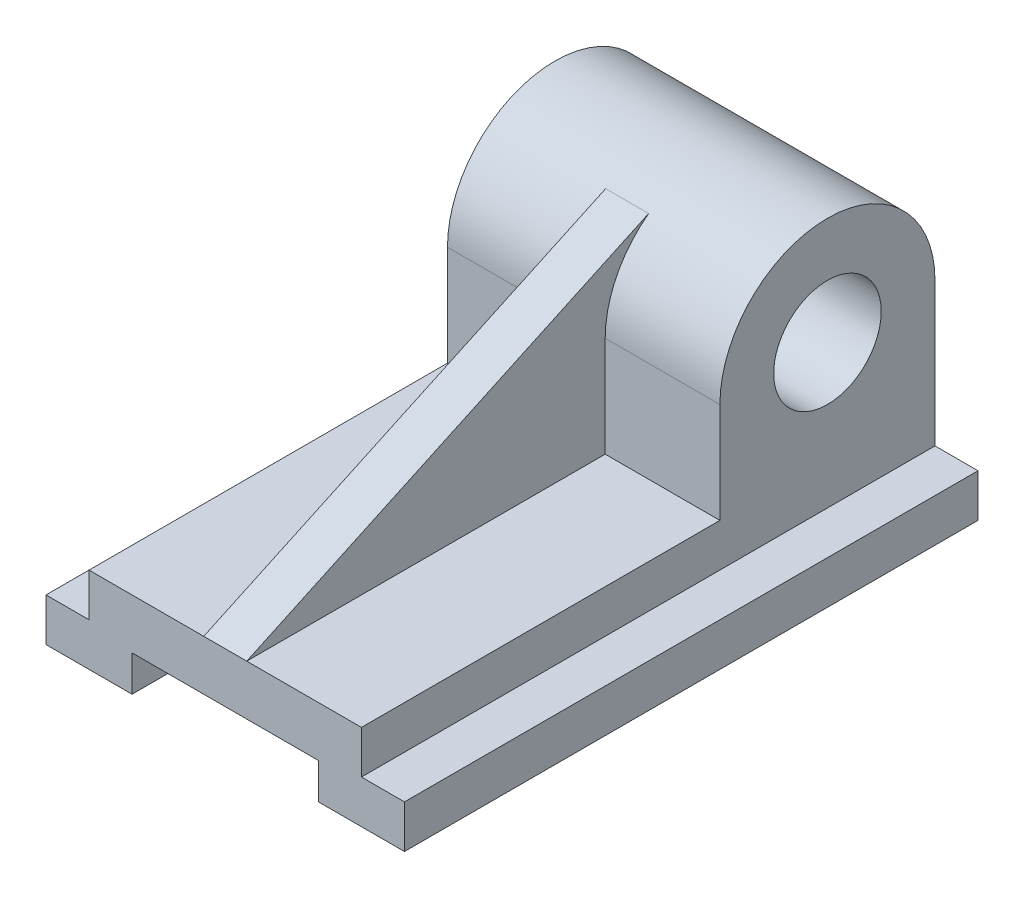
SolidWorks part; units mm, degrees
ref_plane "Front Plane" through (0, 0, 0) normal (0, 0, 1) x (1, 0, 0)
ref_plane "Top Plane" through (0, 0, 0) normal (0, 1, 0) x (1, 0, 0)
ref_plane "Right Plane" through (0, 0, 0) normal (1, 0, 0) x (0, 0, -1)
sketch "Sketch1" plane through (0, 0, 0) normal (0, 0, 1) x (1, 0, 0)
  line L0 (0, 55.322) -> (0, -47.5932) construction
  line L1 (0, 0) -> (-38, 0)
  line L2 (-38, 0) -> (-38, -12)
  line L3 (-38, -12) -> (-50, -12)
  line L4 (-50, -12) -> (-50, -24)
  line L5 (-50, -24) -> (-26, -24)
  line L6 (-26, -24) -> (-26, -14)
  line L7 (-26, -14) -> (26, -14)
  line L8 (26, -14) -> (26, -24)
  line L9 (26, -24) -> (50, -24)
  line L10 (50, -24) -> (50, -12)
  line L11 (50, -12) -> (38, -12)
  line L12 (38, -12) -> (38, 0)
  line L13 (38, 0) -> (0, 0)
  point P13 (44, -12)
  dimension "D1" = 24
  dimension "D2" = 38
  dimension "D3" = 12
  dimension "D4" = 12
  dimension "D5" = 12
  dimension "D6" = 10
extrude "Boss-Extrude1" add sketch "Sketch1" along normal blind 160
sketch "Sketch2" plane through (38, 0, 0) normal (1, 0, 0) x (0, 0, -1)
  line L0 (0, 0) -> (0, 28)
  line L1 (-60, 0) -> (-60, 28)
  line L2 (-160, 0) -> (0, 0) construction
  arc A0 (0, 28) -> (-60, 28) centre (-30, 28) ccw
  circle A1 centre (-30, 28) radius 15
  line M3 (0, 0) -> (-160, 0)
  dimension "D1" = 30
  dimension "D2" = 30
  dimension "D3" = 28
extrude "Boss-Extrude9" add sketch "Sketch2" against normal blind 76 contours L0 A0 L1 A1 M3
sketch "Sketch6" plane through (0, 0, 0) normal (0, 1, 0) x (1, 0, 0)
  line L0 (0, -1.7861) -> (0, -173.9757) construction
  line L1 (-6, -47.8817) -> (-6, -160)
  line L2 (38, -160) -> (-38, -160) construction
  line L3 (-6, -160) -> (6, -160)
  line L4 (6, -160) -> (6, -47.8817)
  line L5 (6, -47.8817) -> (-6, -47.8817)
  line L6 (-38, 0) -> (38, 0) construction
  dimension "D1" = 12
extrude "Boss-Extrude10" add sketch "Sketch6" along normal blind 72
sketch "Sketch7" plane through (0, 0, 0) normal (1, 0, 0) x (0, 0, -1)
  line L0 (-47.8817, 52.0882) -> (-160, 0)
  line L1 (-47.8817, 52.0882) -> (-47.8817, 72)
  line L2 (-47.8817, 72) -> (-160, 72)
  line L3 (-160, 72) -> (-160, 0)
extrude "Cut-Extrude6" cut sketch "Sketch7" against normal through all both and the other way through all
